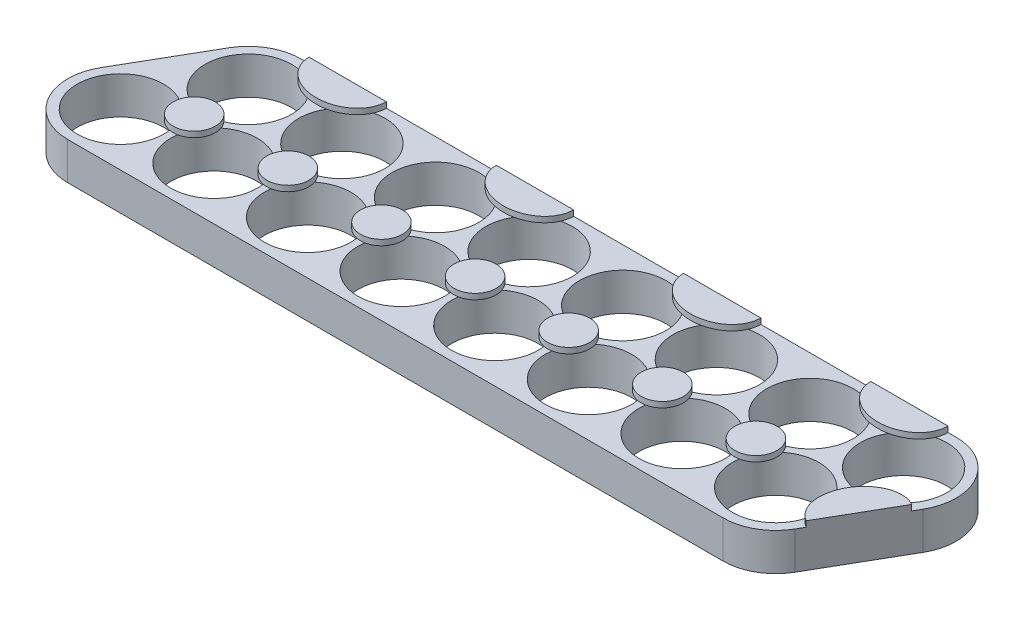
SolidWorks part; units mm, degrees
ref_plane "Front Plane" through (0, 0, 0) normal (0, 0, 1) x (1, 0, 0)
ref_plane "Top Plane" through (0, 0, 0) normal (0, 1, 0) x (1, 0, 0)
ref_plane "Right Plane" through (0, 0, 0) normal (1, 0, 0) x (0, 0, -1)
sketch "Sketch2" plane through (0, 0, 0) normal (0, 1, 0) x (1, 0, 0)
  line L0 (10, 17.3205) -> (0, 0) construction
  line L1 (0, 0) -> (20, 0) construction
  line L2 (20, 0) -> (10, 17.3205) construction
  line L3 (0.2572, 22.9455) -> (-9.7428, 5.625)
  line L4 (0, -11.25) -> (140, -11.25)
  line L5 (20, 0) -> (40, 0) construction
  line L6 (10, 17.3205) -> (30, 17.3205) construction
  line L7 (50, 17.3205) -> (30, 17.3205) construction
  line L8 (10, 28.5705) -> (150, 28.5705)
  line L9 (159.7428, 11.6955) -> (149.7428, -5.625)
  circle A0 centre (10, 17.3205) radius 9.25
  circle A1 centre (0, 0) radius 9.25
  circle A2 centre (20, 0) radius 9.25
  arc A5 (-9.7428, 5.625) -> (0, -11.25) centre (0, 0) ccw
  arc A6 (140, -11.25) -> (149.7428, -5.625) centre (140, 0) ccw
  circle A10 centre (40, 0) radius 9.25
  circle A11 centre (60, 0) radius 9.25
  circle A12 centre (80, 0) radius 9.25
  circle A13 centre (100, 0) radius 9.25
  circle A14 centre (120, 0) radius 9.25
  circle A15 centre (140, 0) radius 9.25
  circle A16 centre (30, 17.3205) radius 9.25
  circle A17 centre (50, 17.3205) radius 9.25
  circle A18 centre (70, 17.3205) radius 9.25
  circle A19 centre (90, 17.3205) radius 9.25
  circle A20 centre (110, 17.3205) radius 9.25
  circle A21 centre (130, 17.3205) radius 9.25
  circle A22 centre (150, 17.3205) radius 9.25
  arc A23 (159.7428, 11.6955) -> (150, 28.5705) centre (150, 17.3205) ccw
  arc A25 (10, 28.5705) -> (0.2572, 22.9455) centre (10, 17.3205) ccw
  point P7 (10, 0)
  dimension "D1" = 18.5
  dimension "D2" = 1.5
  dimension "D3" = 1.5
  dimension "D4" = 7
  dimension "D6" = 2
  dimension "D8" = 172.5
  dimension "D7" = 39.8205
  dimension "D9" = 20
  dimension "D5" = 7
extrude "Boss-Extrude1" add sketch "Sketch2" along normal mid plane 8
sketch "Sketch3" plane through (0, 4, 0) normal (0, 1, 0) x (1, 0, 0)
  line L0 (10, 17.3205) -> (10, 5.7735) construction
  line L1 (10, 5.7735) -> (0, 0) construction
  line L2 (0, 0) -> (20, 0) construction
  line L3 (130, 17.3205) -> (130, 5.7735) construction
  line L4 (130, 5.7735) -> (140, 0) construction
  line L5 (10, 17.3205) -> (20, 11.547) construction
  line L6 (150, 28.5705) -> (10, 28.5705) construction
  line L7 (-3.4641, 2) -> (3.4641, -2) construction
  line L8 (0, 4) -> (20, 4) construction
  line L9 (0, 4) -> (0, -4) construction
  line L10 (0, -4) -> (20, -4) construction
  line L11 (20, 4) -> (20, -4) construction
  line L12 (-3.4641, 2) -> (6.5359, 19.3205) construction
  line L13 (3.4641, -2) -> (13.4641, 15.3205) construction
  line L14 (6.5359, 19.3205) -> (13.4641, 15.3205) construction
  line L15 (13.4641, 19.3205) -> (6.5359, 15.3205) construction
  line L16 (13.4641, 19.3205) -> (23.4641, 2) construction
  line L17 (6.5359, 15.3205) -> (16.5359, -2) construction
  line L18 (23.4641, 2) -> (16.5359, -2) construction
  line L19 (30, 13.3205) -> (10, 13.3205) construction
  line L20 (30, 13.3205) -> (30, 21.3205) construction
  line L21 (30, 21.3205) -> (10, 21.3205) construction
  line L22 (10, 13.3205) -> (10, 21.3205) construction
  line L23 (28.25, 28.5705) -> (11.75, 28.5705)
  line L30 (68.25, 28.5705) -> (51.75, 28.5705)
  line L31 (108.25, 28.5705) -> (91.75, 28.5705)
  line L32 (148.25, 28.5705) -> (131.75, 28.5705)
  line L36 (149.7428, -5.625) -> (159.7428, 11.6955) construction
  line L37 (158.8678, 10.18) -> (150.6178, -4.1095)
  line L38 (20, 28.5705) -> (20, 21.8205) construction
  line L39 (154.7428, 3.0353) -> (148.8971, 6.4103) construction
  line L40 (148.8971, 6.4103) -> (130, 17.3205) construction
  circle A0 centre (10, 5.7735) radius 4.5
  circle A4 centre (30, 5.7735) radius 4.5
  circle A5 centre (50, 5.7735) radius 4.5
  circle A6 centre (70, 5.7735) radius 4.5
  circle A7 centre (90, 5.7735) radius 4.5
  circle A8 centre (110, 5.7735) radius 4.5
  circle A9 centre (130, 5.7735) radius 4.5
  ellipse E0 centre (20, 28.5705) end of major axis (28.25, 28.5705) minor radius 6.75 (11.75, 28.5705) -> (28.25, 28.5705) ccw
  ellipse E1 centre (60, 28.5705) end of major axis (68.25, 28.5705) minor radius 6.75 (51.75, 28.5705) -> (68.25, 28.5705) ccw
  ellipse E2 centre (100, 28.5705) end of major axis (108.25, 28.5705) minor radius 6.75 (91.75, 28.5705) -> (108.25, 28.5705) ccw
  ellipse E3 centre (140, 28.5705) end of major axis (148.25, 28.5705) minor radius 6.75 (131.75, 28.5705) -> (148.25, 28.5705) ccw
  ellipse E4 centre (154.7428, 3.0353) end of major axis (158.8678, 10.18) minor radius 6.75 (158.8678, 10.18) -> (150.6178, -4.1095) ccw
  point P27 (10, 17.3205)
  point P46 (0, 0)
  point P49 (10, 17.3205)
  point P55 (10, 17.3205)
  point P58 (20, 0)
  dimension "D1" = 4
  dimension "D3" = 0.5
  dimension "D6" = 9
  dimension "D4" = 8
  dimension "D5" = 16.5
  dimension "D2" = 7
extrude "Boss-Extrude2" add sketch "Sketch3" along normal blind 1.2
mirror "Mirror1" [suppressed]
sketch "Sketch5" [suppressed] plane through (0, 0, 0) normal (0, 0, 1) x (1, 0, 0)
  line L0 (161.25, -4) -> (161.25, 4) construction
  line L1 (-11.25, -4) -> (161.25, -4)
  line L2 (-11.25, -4) -> (-11.25, 5.2)
  line L3 (-11.25, 5.2) -> (161.25, 5.2)
  line L4 (161.25, -4) -> (161.25, 5.2)
  line L5 (-11.25, -4) -> (161.25, 5.2) construction
  line L6 (-11.25, 5.2) -> (161.25, -4) construction
  line L7 (114.5, 5.2) -> (105.5, 5.2) construction
  point P4 (75, 0.6)
extrude "Cut-Extrude1" [suppressed] cut sketch "Sketch5" against normal through all both and the other way through all
